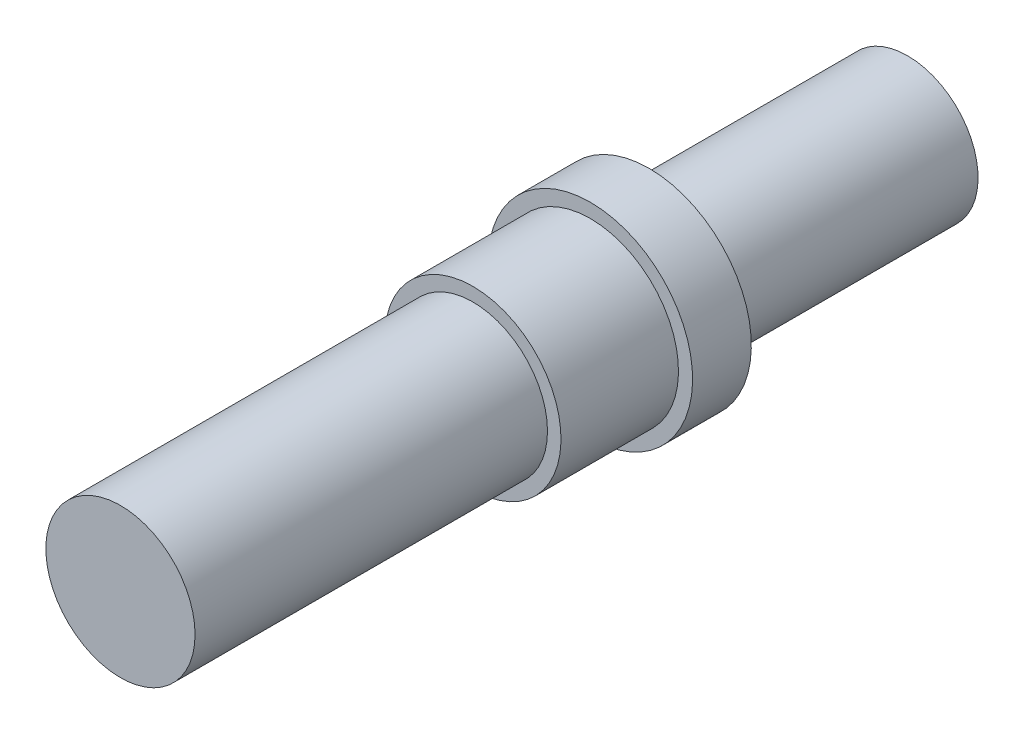
SolidWorks part; units mm, degrees
ref_plane "Front Plane" through (0, 0, 0) normal (0, 0, 1) x (1, 0, 0)
ref_plane "Top Plane" through (0, 0, 0) normal (0, 1, 0) x (1, 0, 0)
ref_plane "Right Plane" through (0, 0, 0) normal (1, 0, 0) x (0, 0, -1)
sketch "Sketch3" plane through (0, 0, 0) normal (1, 0, 0) x (0, 0, -1)
  line L1 (9.9982, 8.7) -> (14.9982, 8.7)
  line L2 (14.9982, 8.7) -> (14.9982, 6)
  line L3 (14.9982, 6) -> (34.9982, 6)
  line L4 (34.9982, 6) -> (34.9982, 0)
  line L5 (34.9982, 0) -> (0, 0)
  line L6 (9.9982, 7.5) -> (-0.0018, 7.5)
  line L7 (-0.0018, 7.5) -> (-0.0018, 0)
  line L8 (-0.0018, 0) -> (0, 0)
  line L9 (9.9982, 7.5) -> (9.9982, 8.7)
  dimension "D1" = 8.7
  dimension "D2" = 6
  dimension "D3" = 20
  dimension "D4" = 5
  dimension "D5" = 10
  dimension "D6" = 7.5
revolve "Initial Resolve -- Exact Length" add sketch "Sketch3" angle 360 about L5
sketch "Sketch5" plane through (0, 0, 0.0018) normal (0, 0, 1) x (1, 0, 0)
  circle A2 centre (0, 0) radius 6.35
  dimension "D1" = 12.7
extrude "Outside Extrude" add sketch "Sketch5" along normal blind 30
sketch "Sketch6" plane through (0, 0, -34.9982) normal (0, 0, -1) x (-1, 0, 0)
  circle A2 centre (0, 0) radius 6
  circle A3 centre (0, 0) radius 6
  dimension "D1" = 0
extrude "Inside Extrude" add sketch "Sketch6" along normal blind 2
